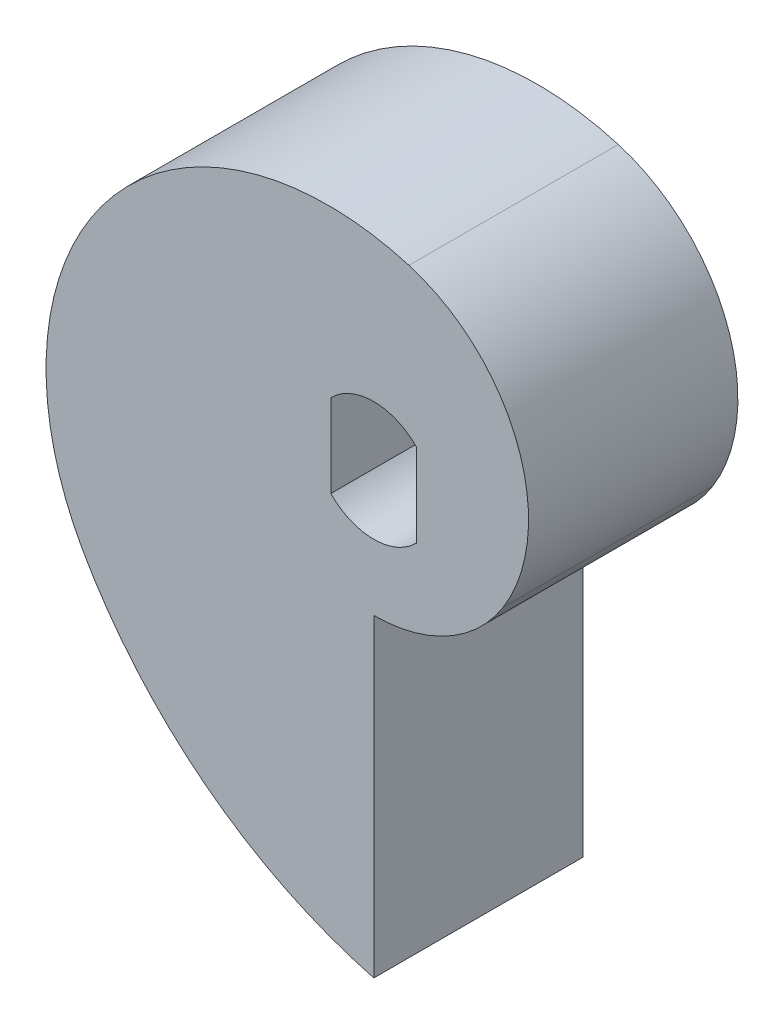
SolidWorks part; units mm, degrees
ref_plane "Спереди" through (0, 0, 0) normal (0, 0, 1) x (1, 0, 0)
ref_plane "Сверху" through (0, 0, 0) normal (0, 1, 0) x (1, 0, 0)
ref_plane "Справа" through (0, 0, 0) normal (1, 0, 0) x (0, 0, -1)
sketch "Эскиз1" plane through (0, 0, 0) normal (0, 0, 1) x (1, 0, 0)
  line L0 (-2.05, 1.9799) -> (-2.05, -1.9799)
  line L1 (2.05, 1.9799) -> (2.05, -1.9799)
  line L2 (0, -6) -> (0, -21)
  arc A1 (-2.05, -1.9799) -> (2.05, -1.9799) centre (0, 0) ccw
  arc A2 (2.05, 1.9799) -> (-2.05, 1.9799) centre (0, 0) ccw
  arc A5 (6.1817, -2.5726) -> (0, -6) centre (0, 1.2885) cw
  arc A6 (1.6813, 9.3245) -> (6.1817, -2.5726) centre (-0.5986, 1.6623) cw
  arc A7 (-13.9292, -10.2075) -> (1.6813, 9.3245) centre (-2.1658, -3.6049) cw
  arc A8 (0, -21) -> (-13.9292, -10.2075) centre (5.7941, 0.863) cw
  point P8 (0, 0)
  point P16 (0, 0)
  point P18 (8.9162, -0.6451)
  point P19 (-0.2809, -25.9975)
  point P20 (0, 0)
  point P21 (0, 0)
  point P22 (0, 0)
  point P23 (-11.109, 9.1879)
  point P24 (6, 7.5108)
  dimension "D1" = 5.7
  dimension "D2" = 4.1
  dimension "D4" = 15
extrude "Основа" add sketch "Эскиз1" along normal blind 10
